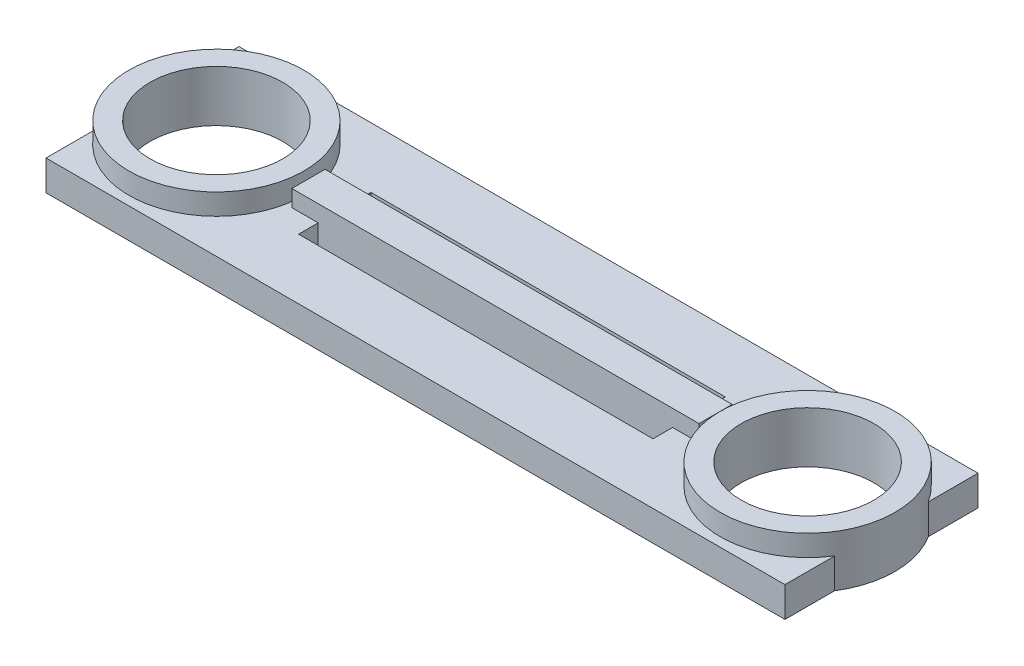
SolidWorks part; units mm, degrees
ref_plane "前视基准面" through (0, 0, 0) normal (0, 0, 1) x (1, 0, 0)
ref_plane "上视基准面" through (0, 0, 0) normal (0, 1, 0) x (1, 0, 0)
ref_plane "右视基准面" through (0, 0, 0) normal (1, 0, 0) x (0, 0, -1)
other "Configuration Table"
sketch "01_Link_Profile" plane through (0, 0, 0) normal (0, 1, 0) x (1, 0, 0)
  line L1 (-245, -64) -> (245, -64)
  line L2 (-245, -64) -> (-245, 64)
  line L3 (-245, 64) -> (245, 64)
  line L4 (245, -64) -> (245, 64)
  line L5 (-245, -64) -> (245, 64) construction
  line L6 (-245, 64) -> (245, -64) construction
  line L7 (-117.5, -24) -> (117.5, -24)
  line L8 (-117.5, -24) -> (-117.5, 24)
  line L9 (-117.5, 24) -> (117.5, 24)
  line L10 (117.5, -24) -> (117.5, 24)
  line L11 (-117.5, -24) -> (117.5, 24) construction
  line L12 (-117.5, 24) -> (117.5, -24) construction
  circle A0 centre (-196, 0) radius 44
  circle A1 centre (196, 0) radius 44
  point P0 (0, 0)
  point P10 (0, 0)
extrude "01_Link_Plate" add sketch "01_Link_Profile" along normal blind 20
sketch "02_End_Boss_Profiles" plane through (0, 0, 0) normal (0, 1, 0) x (1, 0, 0)
  circle A0 centre (-196, 0) radius 58
  circle A1 centre (-196, 0) radius 44
  circle A2 centre (196, 0) radius 58
  circle A3 centre (196, 0) radius 44
extrude "02_Bearing_Seat_Bosses" add sketch "02_End_Boss_Profiles" along normal blind 34
sketch "03_Center_Rib_Profile" plane through (0, 0, 0) normal (0, 1, 0) x (1, 0, 0)
  line L1 (-135, -11) -> (135, -11)
  line L2 (-135, -11) -> (-135, 11)
  line L3 (-135, 11) -> (135, 11)
  line L4 (135, -11) -> (135, 11)
  line L5 (-135, -11) -> (135, 11) construction
  line L6 (-135, 11) -> (135, -11) construction
  point P0 (0, 0)
extrude "03_Center_Rib" add sketch "03_Center_Rib_Profile" along normal blind 31
